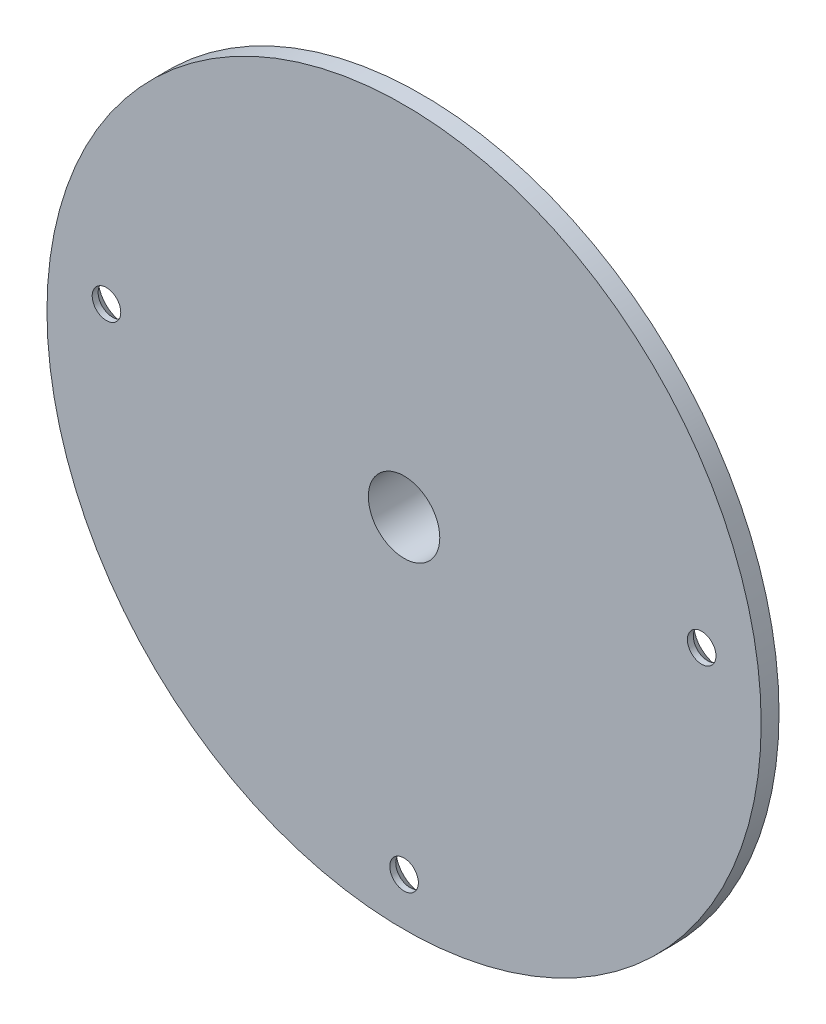
SolidWorks part; units mm, degrees
ref_plane "Piano frontale" through (0, 0, 0) normal (0, 0, 1) x (1, 0, 0)
ref_plane "Piano superiore" through (0, 0, 0) normal (0, 1, 0) x (1, 0, 0)
ref_plane "Piano destro" through (0, 0, 0) normal (1, 0, 0) x (0, 0, -1)
sketch "Schizzo1" plane through (0, 0, 0) normal (0, 0, 1) x (1, 0, 0)
  circle A0 centre (0, 0) radius 30
  circle A1 centre (0, 0) radius 3
  dimension "D1" = 60
  dimension "D2" = 6
extrude "Estrusione-Estrusione1" add sketch "Schizzo1" along normal blind 1.5
hole_wizard "Foro svasato per Vite M2-1" positions "Schizzo3" profile "Schizzo4" countersink size "M2" standard "ISO"
sketch "Schizzo3" plane through (0, 0, 0) normal (0, 0, -1) x (-1, 0, 0)
  line L0 (0, 30) -> (0, -30) construction
  circle A0 centre (0, 0) radius 30 construction
  point P0 (0, -26)
  point P2 (-25, 3)
  point P4 (25, 3)
  dimension "D1" = 50
  dimension "D2" = 3
  dimension "D3" = 26
sketch "Schizzo4" plane through (0, -26, 0) normal (1, 0, 0) x (0, 1, 0)
  line L0 (0, 0) -> (0, 6.721)
  line L1 (0, 6.721) -> (1.2, 6)
  line L2 (1.2, 6) -> (1.2, 1)
  line L3 (1.2, 1) -> (2.2, 0)
  line L5 (2.2, 0) -> (0, 0)
  line L6 (-1.2, 1) -> (-2.2, 0) construction
  line L10 (0, 6.721) -> (-1.2, 6) construction
  line L11 (0, -6.35) -> (0, 107.95) construction
  dimension "Hole Dia." = 2.4
  dimension "Hole Depth" = 6
  dimension "Near C'Sink Dia." = 4.4
  dimension "Near C'Sink Angle" = 90
  dimension "Drill Angle" = 118
sketch "Schizzo5" plane through (0, 0, 0) normal (0, 0, -1) x (-1, 0, 0)
  circle A0 centre (0, 0) radius 4.5
  circle A1 centre (0, 0) radius 3
  dimension "D1" = 9
extrude "Estrusione-Estrusione2" add sketch "Schizzo5" along normal blind 4 contours A0
sketch "Schizzo9" plane through (0, 0, -4) normal (0, 0, -1) x (-1, 0, 0)
  circle A0 centre (0, 0) radius 3
  dimension "D1" = 6
extrude "Taglio-Estrusione1" cut sketch "Schizzo9" against normal blind 10
hole_wizard "Foro per Vite M4-1" positions "Schizzo3D3" profile "Schizzo12" hole size "M4" standard "ISO"
sketch3d "Schizzo3D3"
  point P0 (0.0733, -4.9995, -4.3799)
sketch "Schizzo12" plane through (0.0733, -4.9995, -4.3799) normal (0, 0, 1) x (0.9999, 0.0147, 0)
  line L0 (0, 0) -> (0, 7.3519)
  line L1 (0, 7.3519) -> (2.25, 6)
  line L2 (2.25, 6) -> (2.25, 0)
  line L5 (2.25, 0) -> (0, 0)
  line L10 (0, 7.3519) -> (-2.25, 6) construction
  line L11 (0, -6.35) -> (0, 107.95) construction
  dimension "Hole Dia." = 4.5
  dimension "Hole Depth" = 6
  dimension "Drill Angle" = 118
